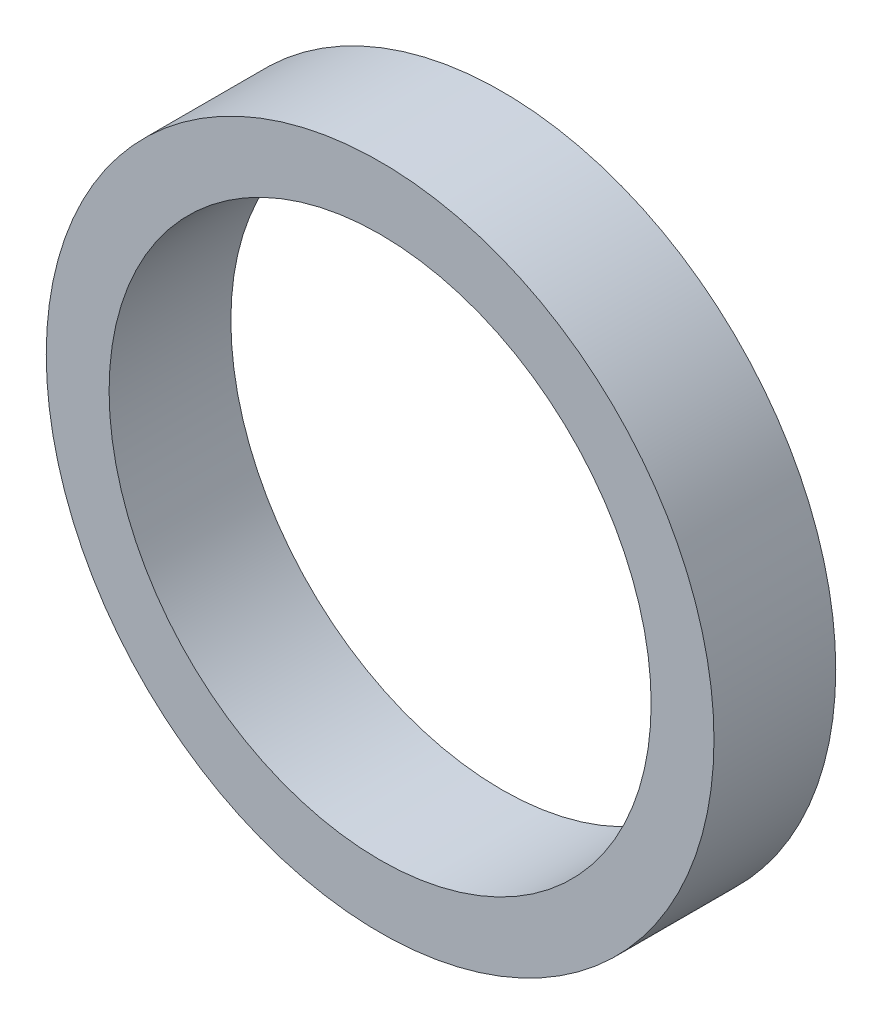
SolidWorks part; units mm, degrees
ref_plane "정면" through (0, 0, 0) normal (0, 0, 1) x (1, 0, 0)
ref_plane "윗면" through (0, 0, 0) normal (0, 1, 0) x (1, 0, 0)
ref_plane "우측면" through (0, 0, 0) normal (1, 0, 0) x (0, 0, -1)
sketch "스케치1" plane through (0, 0, 0) normal (0, 0, 1) x (1, 0, 0)
  circle A0 centre (0, 0) radius 13.8
  circle A1 centre (0, 0) radius 17
  dimension "D1" = 27.6
  dimension "D2" = 34
extrude "보스-돌출1" add sketch "스케치1" along normal blind 6.2
